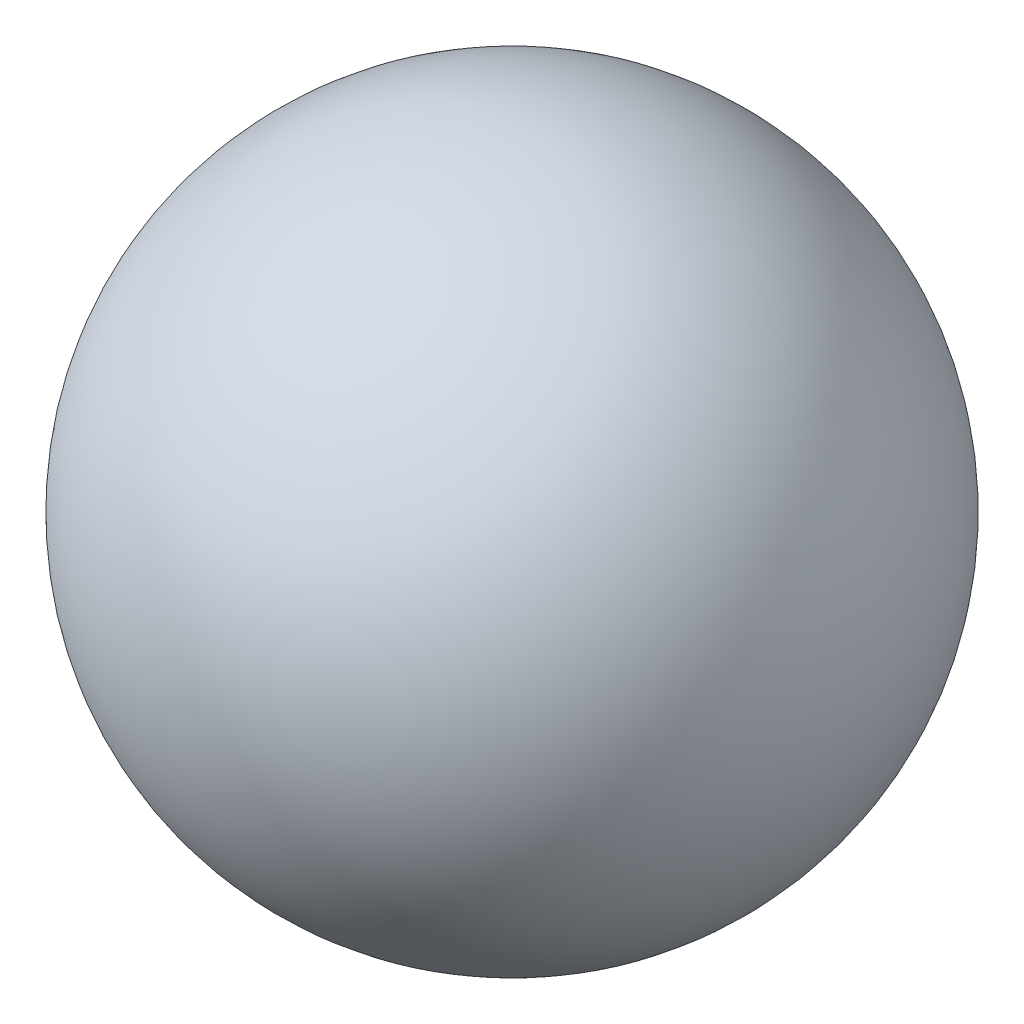
SolidWorks part; units mm, degrees
ref_plane "Front" through (0, 0, 0) normal (0, 0, 1) x (1, 0, 0)
ref_plane "Top" through (0, 0, 0) normal (0, 1, 0) x (1, 0, 0)
ref_plane "Right" through (0, 0, 0) normal (1, 0, 0) x (0, 0, -1)
sketch "草图1" plane through (0, 0, 0) normal (0, 0, 1) x (1, 0, 0)
  line L0 (0, 2.77) -> (0, -2.77)
  arc A0 (0, -2.77) -> (0, 2.77) centre (0, 0) ccw
revolve "旋转1" add sketch "草图1" angle 360 about L0
